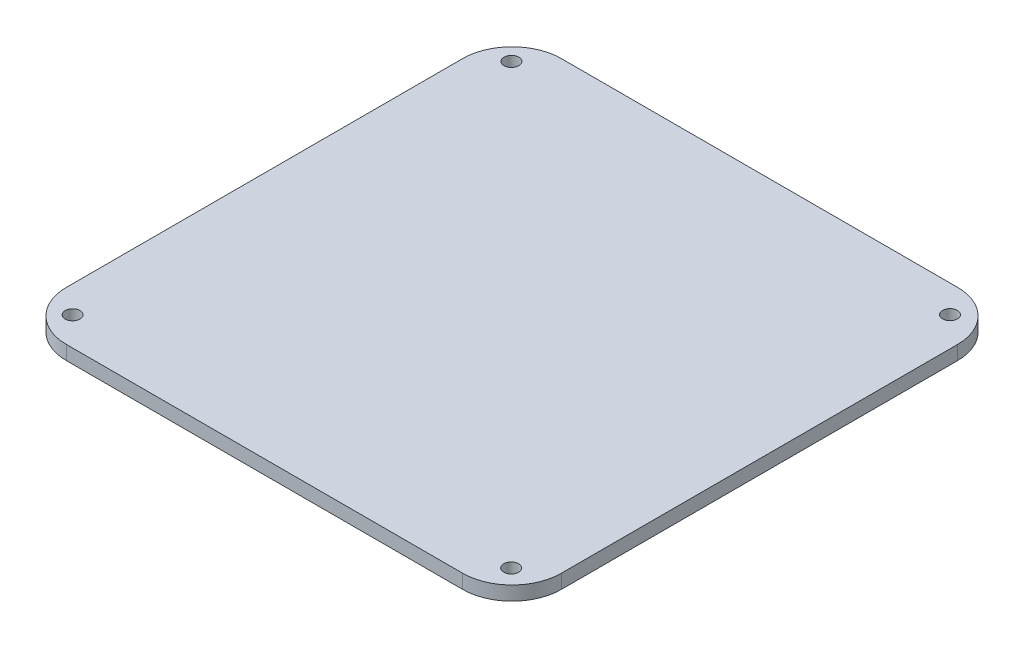
SolidWorks part; units mm, degrees
ref_plane "Front Plane" through (0, 0, 0) normal (0, 0, 1) x (1, 0, 0)
ref_plane "Top Plane" through (0, 0, 0) normal (0, 1, 0) x (1, 0, 0)
ref_plane "Right Plane" through (0, 0, 0) normal (1, 0, 0) x (0, 0, -1)
sketch "Sketch1" plane through (0, 0, 0) normal (0, 1, 0) x (1, 0, 0)
  line L1 (9, 0) -> (81.3, 0)
  line L2 (0, 9) -> (0, 81.3)
  line L3 (9, 90.3) -> (81.3, 90.3)
  line L4 (90.3, 9) -> (90.3, 81.3)
  arc A0 (90.3, 9) -> (81.3, 0) centre (81.3, 9) cw
  arc A1 (9, 0) -> (0, 9) centre (9, 9) cw
  arc A2 (0, 81.3) -> (9, 90.3) centre (9, 81.3) cw
  arc A3 (81.3, 90.3) -> (90.3, 81.3) centre (81.3, 81.3) cw
  circle A4 centre (4.9, 85.3) radius 1.35
  circle A5 centre (84.9, 85.3) radius 1.35
  circle A6 centre (84.9, 5.25) radius 1.35
  circle A7 centre (4.9, 5.25) radius 1.35
  point P7 (90.3, 0)
  point P10 (0, 0)
  point P15 (90.3, 90.3)
  dimension "D3" = 9
  dimension "D4" = 2.7
  dimension "D1" = 90.3
  dimension "D2" = 90.3
  dimension "D5" = 5.4
  dimension "D6" = 5
  dimension "D7" = 5.4
  dimension "D8" = 5.25
  dimension "D9" = 5.25
  dimension "D10" = 4.9
  dimension "D11" = 4.9
  dimension "D12" = 5
extrude "Boss-Extrude1" add sketch "Sketch1" along normal blind 2.56
